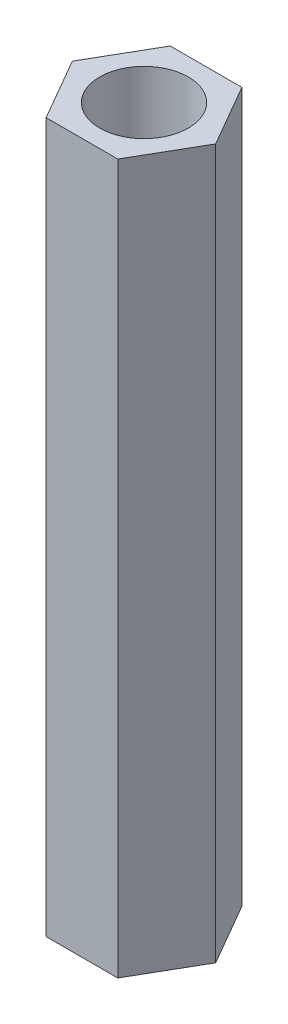
SolidWorks part; units mm, degrees
ref_plane "前视基准面" through (0, 0, 0) normal (0, 0, 1) x (1, 0, 0)
ref_plane "上视基准面" through (0, 0, 0) normal (0, 1, 0) x (1, 0, 0)
ref_plane "右视基准面" through (0, 0, 0) normal (1, 0, 0) x (0, 0, -1)
other "Configuration Table"
sketch "草图1" plane through (0, 0, 0) normal (0, 1, 0) x (1, 0, 0)
  line L1 (2.0207, 3.5) -> (-2.0207, 3.5)
  line L2 (-2.0207, 3.5) -> (-4.0415, 0)
  line L3 (-4.0415, 0) -> (-2.0207, -3.5)
  line L4 (-2.0207, -3.5) -> (2.0207, -3.5)
  line L5 (2.0207, -3.5) -> (4.0415, 0)
  line L6 (4.0415, 0) -> (2.0207, 3.5)
  circle A0 centre (0, 0) radius 3.5 construction
  circle A1 centre (0, 0) radius 2.5
  dimension "D2" = 5
  dimension "D1" = 7
extrude "凸台-拉伸1" add sketch "草图1" along normal blind 40
